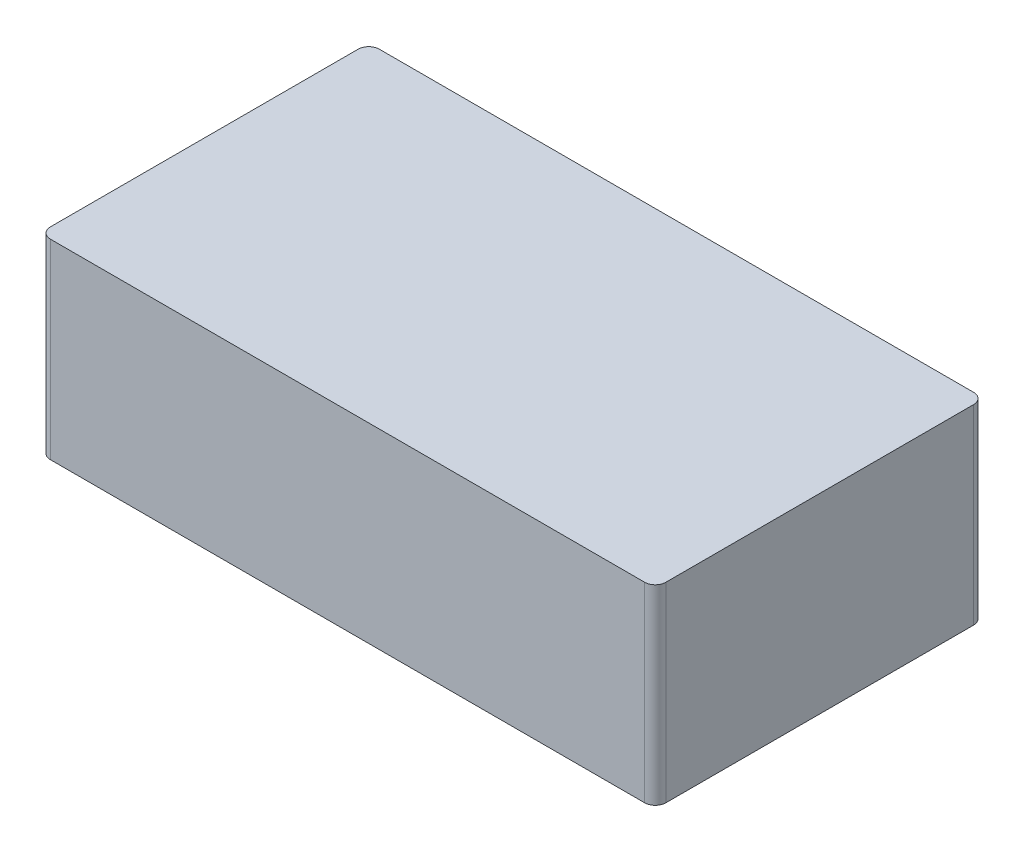
SolidWorks part; units mm, degrees
ref_plane "Front Plane" through (0, 0, 0) normal (0, 0, 1) x (1, 0, 0)
ref_plane "Top Plane" through (0, 0, 0) normal (0, 1, 0) x (1, 0, 0)
ref_plane "Right Plane" through (0, 0, 0) normal (1, 0, 0) x (0, 0, -1)
sketch "Sketch1" plane through (0, 0, 0) normal (0, 1, 0) x (1, 0, 0)
  line L1 (0, 0) -> (58, 0)
  line L2 (0, 0) -> (0, 31)
  line L3 (0, 31) -> (58, 31)
  line L4 (58, 0) -> (58, 31)
  dimension "D1" = 31
  dimension "D2" = 58
extrude "Boss-Extrude1" add sketch "Sketch1" along normal blind 18
fillet "Fillet2" radius 1 4 edges at (0, 9, -31) (58, 9, -31) (58, 9, 0) (0, 9, 0)
